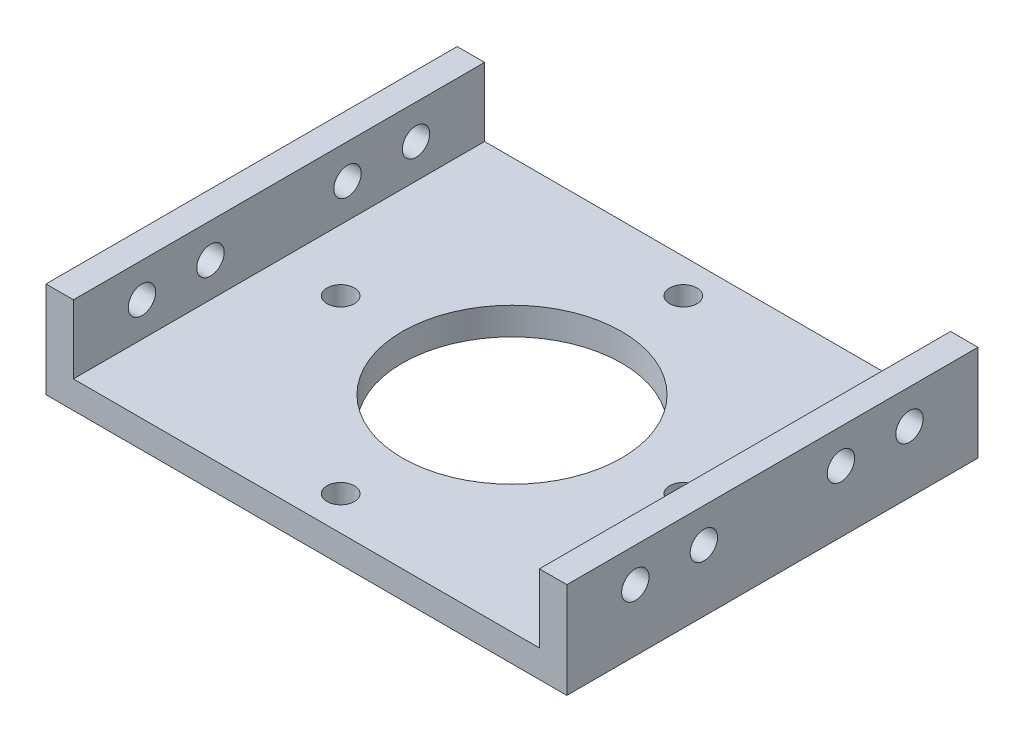
SolidWorks part; units mm, degrees
material "6061 合金"
ref_plane "前视基准面" through (0, 0, 0) normal (0, 0, 1) x (1, 0, 0)
ref_plane "上视基准面" through (0, 0, 0) normal (0, 1, 0) x (1, 0, 0)
ref_plane "右视基准面" through (0, 0, 0) normal (1, 0, 0) x (0, 0, -1)
sketch "草图1" plane through (0, 0, 0) normal (0, 0, 1) x (1, 0, 0)
  line L0 (0, 47.6325) -> (0, -53.9266) construction
  line L1 (38, 0) -> (-38, 0)
  line L2 (-38, 0) -> (-38, 14)
  line L3 (-38, 14) -> (-34, 14)
  line L4 (-34, 14) -> (-34, 4)
  line L5 (-34, 4) -> (34, 4)
  line L7 (34, 14) -> (34, 4)
  line L8 (38, 14) -> (34, 14)
  line L9 (38, 0) -> (38, 14)
  point P10 (0, 4)
  point P11 (0, 0)
extrude "凸台-拉伸1" add sketch "草图1" along normal mid plane 60
sketch "草图2" plane through (38, 0, 0) normal (1, 0, 0) x (0, 0, -1)
  line L0 (-30, 0) -> (-30, 9) construction
  line L1 (-30, 0) -> (-30, 14) construction
  line L2 (0, 19.6652) -> (0, -8.571) construction
  line L4 (-30, 9) -> (-20, 9) construction
  line L5 (-20, 9) -> (-10, 9) construction
  circle A4 centre (-20, 9) radius 2
  circle A5 centre (-10, 9) radius 2
  circle A6 centre (10, 9) radius 2
  circle A7 centre (20, 9) radius 2
  dimension "D2" = 10
  dimension "D1" = 9
  dimension "D3" = 10
extrude "切除-拉伸1" cut sketch "草图2" against normal up to surface (76 mm away) up to face at (-38, 7, 0)
sketch "草图3" plane through (0, 4, 0) normal (0, 1, 0) x (1, 0, 0)
  circle A0 centre (0, 0) radius 16
  circle A1 centre (0, 0) radius 25 construction
  circle A2 centre (0, 25) radius 2
  circle A3 centre (25, 0) radius 2
  circle A4 centre (0, -25) radius 2
  circle A5 centre (-25, 0) radius 2
  point P15 (0, 0)
  dimension "D1" = 4
extrude "切除-拉伸2" cut sketch "草图3" against normal up to surface (4 mm away) up to face at (0, 0, 0)
